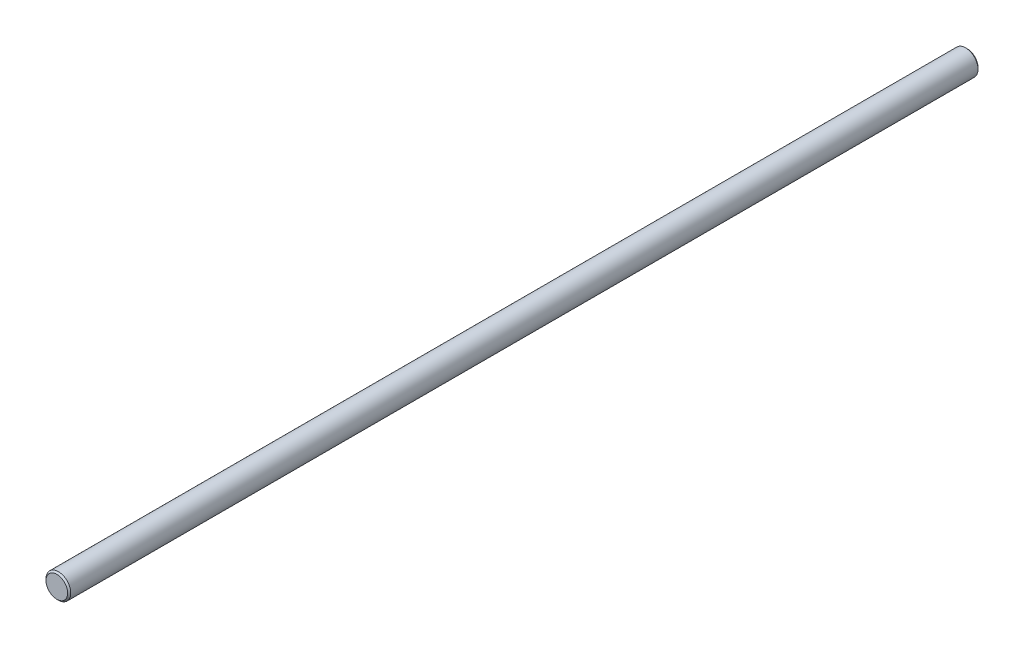
SolidWorks part; units mm, degrees
ref_plane "Front Plane" through (0, 0, 0) normal (0, 0, 1) x (1, 0, 0)
ref_plane "Top Plane" through (0, 0, 0) normal (0, 1, 0) x (1, 0, 0)
ref_plane "Right Plane" through (0, 0, 0) normal (1, 0, 0) x (0, 0, -1)
ref_plane "Plane1" through (0, 0, 0) normal (0, -1, 0) x (1, 0, 0)
sketch "Sketch1" plane through (0, 0, 0) normal (0, -1, 0) x (1, 0, 0)
  line L0 (3.5, 294) -> (0, 294)
  line L1 (0, 294) -> (0, 0)
  line L2 (0, 0) -> (3.5, 0)
  line L3 (3.5, 0) -> (4, 0.5)
  line L4 (4, 0.5) -> (4, 293.5)
  line L5 (4, 293.5) -> (3.5, 294)
  line L6 (0, 294) -> (0, 0) construction
revolve "Revolve1" add sketch "Sketch1" angle 360 about L6
